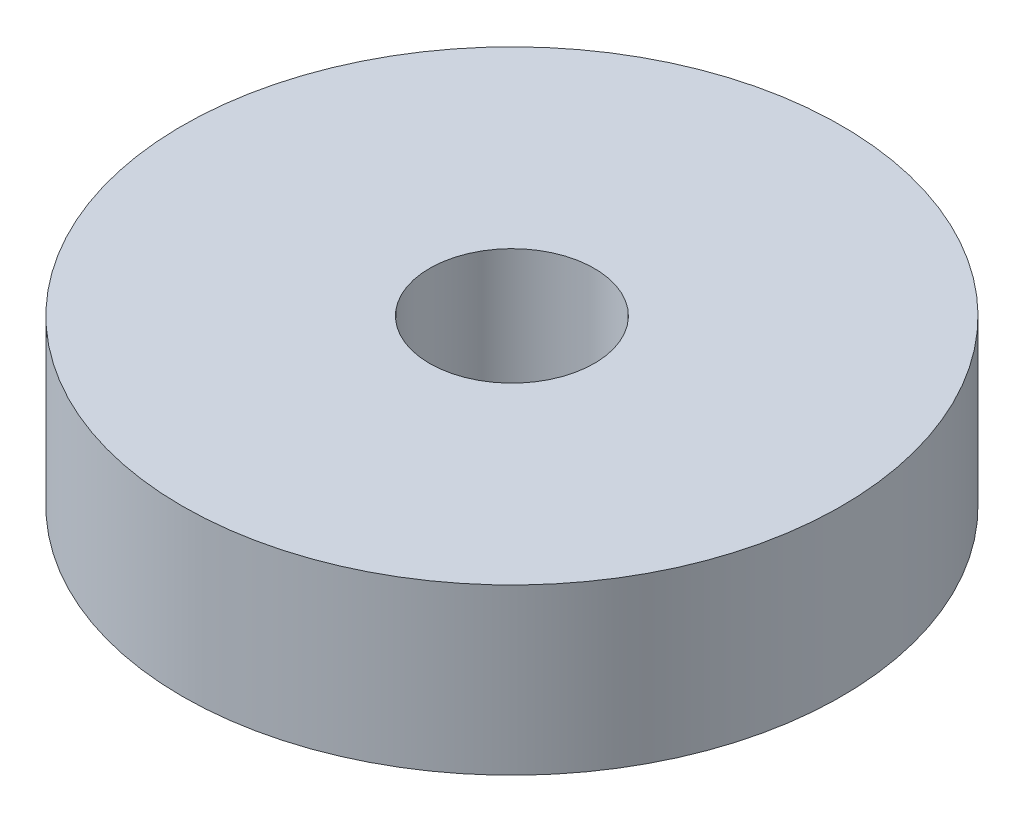
SolidWorks part; units mm, degrees
material "Plain Carbon Steel"
ref_plane "Front Plane" through (0, 0, 0) normal (0, 0, 1) x (1, 0, 0)
ref_plane "Top Plane" through (0, 0, 0) normal (0, 1, 0) x (1, 0, 0)
ref_plane "Right Plane" through (0, 0, 0) normal (1, 0, 0) x (0, 0, -1)
sketch "Sketch1" plane through (0, 0, 0) normal (0, 1, 0) x (1, 0, 0)
  circle A0 centre (0, 0) radius 100
  dimension "D1" = 200
extrude "Boss-Extrude2" add sketch "Sketch1" along normal blind 50
sketch "Sketch2" plane through (0, 50, 0) normal (0, 1, 0) x (1, 0, 0)
  circle A0 centre (0, 0) radius 25
  dimension "D1" = 50
extrude "Cut-Extrude1" cut sketch "Sketch2" against normal blind 50
